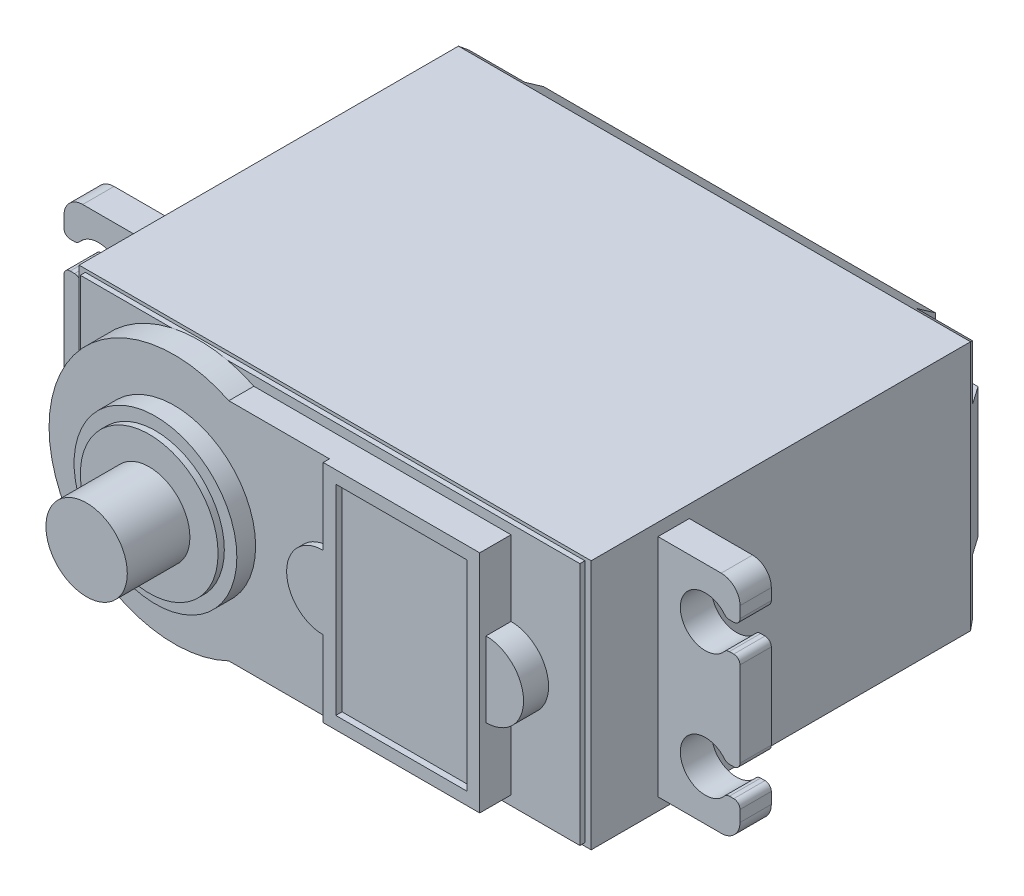
SolidWorks part; units mm, degrees
ref_plane "Front Plane" through (0, 0, 0) normal (0, 0, 1) x (1, 0, 0)
ref_plane "Top Plane" through (0, 0, 0) normal (0, 1, 0) x (1, 0, 0)
ref_plane "Right Plane" through (0, 0, 0) normal (1, 0, 0) x (0, 0, -1)
sketch "Sketch1" plane through (0, 0, 0) normal (0, 0, 1) x (1, 0, 0)
  line L1 (-20.45, 10) -> (20.45, 10)
  line L2 (-20.45, 10) -> (-20.45, -10)
  line L3 (-20.45, -10) -> (20.45, -10)
  line L4 (20.45, 10) -> (20.45, -10)
  line L5 (-20.45, 10) -> (20.45, -10) construction
  line L6 (-20.45, -10) -> (20.45, 10) construction
  point P0 (0, 0)
  dimension "D1" = 40.9
  dimension "D2" = 20
extrude "Boss-Extrude1" add sketch "Sketch1" along normal blind 19.3
sketch "Sketch2" plane through (0, 0, 0) normal (0, 0, -1) x (-1, 0, 0)
  line L4 (-20.45, 10) -> (-20.45, -10)
  line L5 (-20.45, -10) -> (20.45, -10)
  line L6 (20.45, -10) -> (20.45, 10)
  line L7 (20.45, 10) -> (-20.45, 10)
  line L8 (-20.45, 10) -> (-20.45, -10)
  line L9 (-20.45, -10) -> (20.45, -10)
  line L10 (20.45, -10) -> (20.45, 10)
  line L11 (20.45, 10) -> (-20.45, 10)
  dimension "D1" = 0
extrude "Boss-Extrude2" add sketch "Sketch2" along normal blind 6.5
sketch "Sketch3" plane through (0, 0, 19.3) normal (0, 0, 1) x (1, 0, 0)
  line L4 (20.45, -10) -> (20.45, 10)
  line L5 (20.45, 10) -> (-20.45, 10)
  line L6 (-20.45, 10) -> (-20.45, -10)
  line L7 (-20.45, -10) -> (20.45, -10)
  line L8 (20.45, -10) -> (20.45, 10)
  line L9 (20.45, 10) -> (-20.45, 10)
  line L10 (-20.45, 10) -> (-20.45, -10)
  line L11 (-20.45, -10) -> (20.45, -10)
  dimension "D1" = 0
extrude "Boss-Extrude3" add sketch "Sketch3" along normal blind 6.5
chamfer "Chamfer1" distance 2 angle 35 4 edges at (-20.45, 0, -6.5) (0, -10, -6.5) (20.45, 0, -6.5) (0, 10, -6.5)
sketch "Sketch4" plane through (0, 0, -6.5) normal (0, 0, -1) x (-1, 0, 0)
  line L0 (0, 7.838) -> (0, -12.841) construction
  line L1 (-20.45, 10) -> (-15.65, 10)
  line L2 (-20.45, 10) -> (-20.45, 5.2)
  line L3 (-20.45, 5.2) -> (-17.65, 5.2)
  line L4 (-15.65, 10) -> (-15.65, 7.2)
  line L5 (-6.0036, 0) -> (12.9124, 0) construction
  line L6 (15.65, 10) -> (15.65, 7.2)
  line L7 (20.45, 5.2) -> (17.65, 5.2)
  line L8 (20.45, 10) -> (20.45, 5.2)
  line L9 (20.45, 10) -> (15.65, 10)
  line L10 (20.45, -10) -> (15.65, -10)
  line L11 (20.45, -10) -> (20.45, -5.2)
  line L12 (20.45, -5.2) -> (17.65, -5.2)
  line L13 (15.65, -10) -> (15.65, -7.2)
  line L14 (-15.65, -10) -> (-15.65, -7.2)
  line L15 (-20.45, -5.2) -> (-17.65, -5.2)
  line L16 (-20.45, -10) -> (-20.45, -5.2)
  line L17 (-20.45, -10) -> (-15.65, -10)
  arc A0 (-15.65, 7.2) -> (-17.65, 5.2) centre (-17.65, 7.2) cw
  arc A1 (15.65, 7.2) -> (17.65, 5.2) centre (17.65, 7.2) ccw
  arc A2 (15.65, -7.2) -> (17.65, -5.2) centre (17.65, -7.2) cw
  arc A3 (-15.65, -7.2) -> (-17.65, -5.2) centre (-17.65, -7.2) ccw
  dimension "D3" = 2
  dimension "D1" = 4.8
  dimension "D2" = 4.8
extrude "Cut-Extrude1" cut sketch "Sketch4" against normal blind 1.5
sketch "Sketch5" plane through (0, 0, 25.8) normal (0, 0, 1) x (1, 0, 0)
  line L0 (-20.45, 10) -> (-20.45, -10) construction
  line L1 (-19.95, 9.75) -> (19.95, 9.75)
  line L2 (-19.95, 9.75) -> (-19.95, -9.75)
  line L3 (-19.95, -9.75) -> (19.95, -9.75)
  line L4 (19.95, 9.75) -> (19.95, -9.75)
  line L5 (-19.95, 9.75) -> (19.95, -9.75) construction
  line L6 (-19.95, -9.75) -> (19.95, 9.75) construction
  line L7 (20.45, 10) -> (-20.45, 10) construction
  point P0 (0, 0)
  dimension "D1" = 0.5
  dimension "D2" = 0.25
extrude "Boss-Extrude4" add sketch "Sketch5" along normal blind 0.4
sketch "Sketch6" plane through (0, 0, 26.2) normal (0, 0, 1) x (1, 0, 0)
  line L0 (-20.45, 0) -> (20.45, 0) construction
  line L1 (-20.45, 10) -> (-20.45, -10) construction
  line L2 (20.45, -10) -> (20.45, 10) construction
  line L3 (-6.09, 10) -> (-6.09, -10) construction
  line L4 (20.45, 10) -> (-20.45, 10) construction
  line L5 (-20.45, -10) -> (20.45, -10) construction
  line L6 (-6.09, 8.9995) -> (14.45, 8.9995)
  line L8 (14.45, -8.9995) -> (-6.09, -8.9995)
  line L10 (14.45, 8.9995) -> (14.45, 3)
  line L11 (14.45, -3) -> (14.45, -8.9995)
  arc A0 (-6.09, 8.9995) -> (-6.09, -8.9995) centre (-10.45, 0) ccw
  arc A2 (14.45, -3) -> (14.45, 3) centre (14.45, 0) ccw
  point P19 (17.45, 0)
  dimension "D2" = 3
  dimension "D1" = 14.36
  dimension "D3" = 6
extrude "Boss-Extrude5" add sketch "Sketch6" along normal blind 2
sketch "Sketch7" plane through (0, 0, 28.2) normal (0, 0, 1) x (1, 0, 0)
  circle A0 centre (-10.45, 0) radius 6.5
  dimension "D1" = 13
extrude "Boss-Extrude6" add sketch "Sketch7" along normal blind 1.5
sketch "Sketch8" plane through (0, 0, 29.7) normal (0, 0, 1) x (1, 0, 0)
  circle A0 centre (-10.45, 0) radius 5.5
  dimension "D1" = 11
extrude "Boss-Extrude7" add sketch "Sketch8" along normal blind 0.5
sketch "Sketch9" plane through (0, 0, 30.2) normal (0, 0, 1) x (1, 0, 0)
  circle A0 centre (-10.45, 0) radius 3.25
  dimension "D1" = 6.5
extrude "Boss-Extrude8" add sketch "Sketch9" along normal blind 5
sketch "Sketch10" plane through (0, 0, 28.2) normal (0, 0, 1) x (1, 0, 0)
  line L0 (14.45, 8.9995) -> (-6.09, 8.9995) construction
  line L1 (1.95, 8.9995) -> (14.45, 8.9995)
  line L2 (1.95, 8.9995) -> (1.95, 2.925)
  line L3 (1.95, -8.9995) -> (14.45, -8.9995)
  line L4 (14.45, 8.9995) -> (14.45, -8.9995)
  line L5 (2.95, 7.9995) -> (13.45, 7.9995)
  line L6 (13.45, 7.9995) -> (13.45, -7.9995)
  line L7 (2.95, -7.9995) -> (13.45, -7.9995)
  line L8 (2.95, 7.9995) -> (2.95, -7.9995)
  line L9 (1.95, -2.925) -> (1.95, -8.9995)
  line L11 (1.95, 8.9995) -> (1.95, -8.9995) construction
  arc A0 (1.95, 2.925) -> (1.95, -2.925) centre (1.95, 0) ccw
  dimension "D3" = 5.85
  dimension "D1" = 12.5
  dimension "D2" = 1
extrude "Boss-Extrude9" add sketch "Sketch10" along normal blind 0.5
sketch "Sketch11" plane through (0, 0, 26.2) normal (0, 0, 1) x (1, 0, 0)
  line L0 (0, 0) -> (27.9214, 0) construction
  line L1 (20.45, 10) -> (-20.45, 10) construction
  line L2 (20.45, 9) -> (25.5, 9)
  line L3 (20.45, -10) -> (20.45, 10) construction
  line L4 (27, 7.5) -> (27, 6.6015)
  line L5 (26.5, 6.1015) -> (26.1503, 6.1015)
  line L6 (26.5, 3.8985) -> (26.1503, 3.8985)
  line L7 (27, 3.3985) -> (27, -3.3985)
  line L8 (0, 13.0094) -> (0, -12.9082) construction
  line L9 (26.5, -3.8985) -> (26.1503, -3.8985)
  line L10 (26.5, -6.1015) -> (26.1503, -6.1015)
  line L11 (27, -7.5) -> (27, -6.6015)
  line L12 (20.45, -9) -> (25.5, -9)
  line L13 (0, -13.0094) -> (0, 12.9082) construction
  line L14 (-20.45, -9) -> (-25.5, -9)
  line L15 (-27, -7.5) -> (-27, -6.6015)
  line L16 (-26.5, -6.1015) -> (-26.1503, -6.1015)
  line L17 (-26.5, -3.8985) -> (-26.1503, -3.8985)
  line L18 (-27, 3.3985) -> (-27, -3.3985)
  line L19 (-26.5, 3.8985) -> (-26.1503, 3.8985)
  line L20 (-26.5, 6.1015) -> (-26.1503, 6.1015)
  line L21 (-27, 7.5) -> (-27, 6.6015)
  line L22 (-20.45, 9) -> (-25.5, 9)
  line L23 (-20.45, 9) -> (-20.45, -9)
  line L24 (20.45, 9) -> (20.45, -9)
  arc A0 (25.7664, 6.2812) -> (25.7664, 3.7188) centre (24.2307, 5) ccw
  arc A1 (27, 7.5) -> (25.5, 9) centre (25.5, 7.5) ccw
  arc A2 (26.1503, 6.1015) -> (25.7664, 6.2812) centre (26.1503, 6.6015) cw
  arc A3 (27, 6.6015) -> (26.5, 6.1015) centre (26.5, 6.6015) cw
  arc A4 (27, 3.3985) -> (26.5, 3.8985) centre (26.5, 3.3985) ccw
  arc A5 (26.1503, 3.8985) -> (25.7664, 3.7188) centre (26.1503, 3.3985) ccw
  arc A6 (26.1503, -3.8985) -> (25.7664, -3.7188) centre (26.1503, -3.3985) cw
  arc A7 (27, -3.3985) -> (26.5, -3.8985) centre (26.5, -3.3985) cw
  arc A8 (27, -6.6015) -> (26.5, -6.1015) centre (26.5, -6.6015) ccw
  arc A9 (26.1503, -6.1015) -> (25.7664, -6.2812) centre (26.1503, -6.6015) ccw
  arc A10 (27, -7.5) -> (25.5, -9) centre (25.5, -7.5) cw
  arc A11 (25.7664, -6.2812) -> (25.7664, -3.7188) centre (24.2307, -5) cw
  arc A12 (-25.7664, -6.2812) -> (-25.7664, -3.7188) centre (-24.2307, -5) ccw
  arc A13 (-27, -7.5) -> (-25.5, -9) centre (-25.5, -7.5) ccw
  arc A14 (-26.1503, -6.1015) -> (-25.7664, -6.2812) centre (-26.1503, -6.6015) cw
  arc A15 (-27, -6.6015) -> (-26.5, -6.1015) centre (-26.5, -6.6015) cw
  arc A16 (-27, -3.3985) -> (-26.5, -3.8985) centre (-26.5, -3.3985) ccw
  arc A17 (-26.1503, -3.8985) -> (-25.7664, -3.7188) centre (-26.1503, -3.3985) ccw
  arc A18 (-26.1503, 3.8985) -> (-25.7664, 3.7188) centre (-26.1503, 3.3985) cw
  arc A19 (-27, 3.3985) -> (-26.5, 3.8985) centre (-26.5, 3.3985) cw
  arc A20 (-27, 6.6015) -> (-26.5, 6.1015) centre (-26.5, 6.6015) ccw
  arc A21 (-26.1503, 6.1015) -> (-25.7664, 6.2812) centre (-26.1503, 6.6015) ccw
  arc A22 (-27, 7.5) -> (-25.5, 9) centre (-25.5, 7.5) cw
  arc A23 (-25.7664, 6.2812) -> (-25.7664, 3.7188) centre (-24.2307, 5) cw
  point P23 (27, 3.8985)
  point P26 (25.9, 3.8985)
  point P45 (27, 0)
  point P46 (25.9, -3.8985)
  point P47 (27, -3.8985)
  point P84 (-27, -3.8985)
  point P85 (-25.9, -3.8985)
  point P86 (-27, 0)
  point P87 (-25.9, 3.8985)
  point P88 (-27, 3.8985)
  dimension "D3" = 5
  dimension "D4" = 2
  dimension "D6" = 1.5
  dimension "D7" = 0.5
  dimension "D8" = 0.5
  dimension "D1" = 6.55
  dimension "D2" = 1
  dimension "D5" = 1.1
extrude "Boss-Extrude10" add sketch "Sketch11" against normal blind 2.5 from offset 5.74 offset against normal yes
